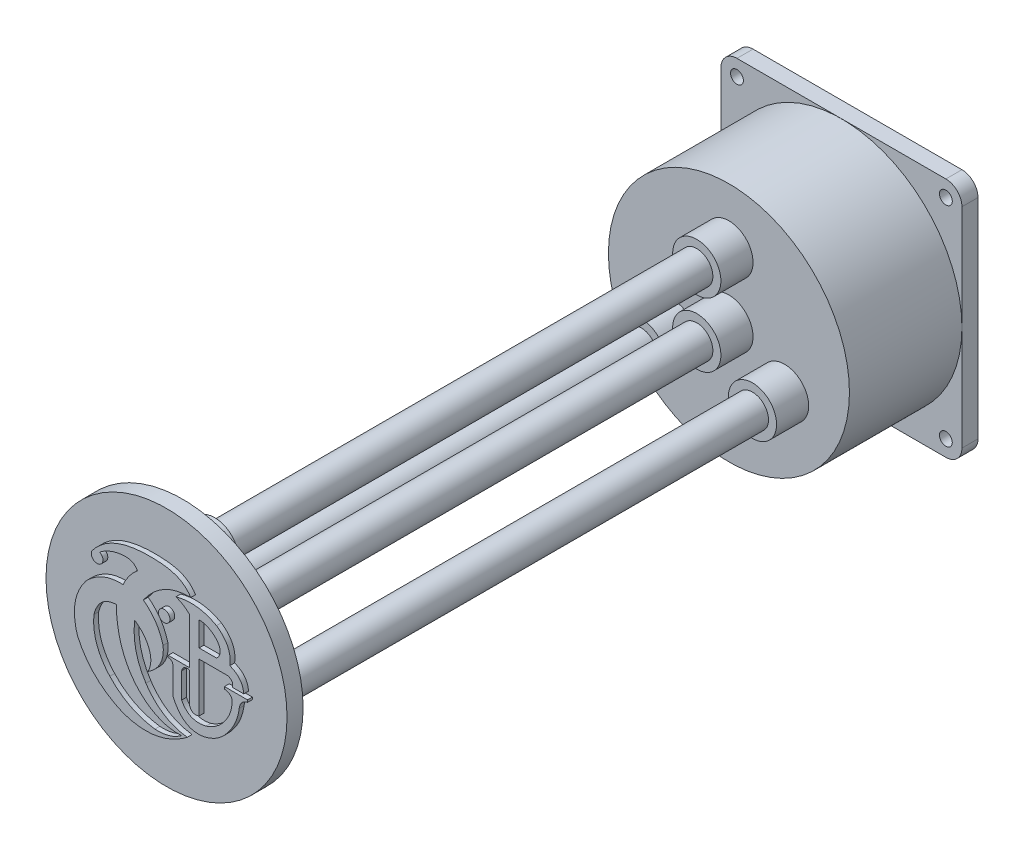
SolidWorks part; units mm, degrees
ref_plane "Plan de face" through (0, 0, 0) normal (0, 0, 1) x (1, 0, 0)
ref_plane "Plan de dessus" through (0, 0, 0) normal (0, 1, 0) x (1, 0, 0)
ref_plane "Plan de droite" through (0, 0, 0) normal (1, 0, 0) x (0, 0, -1)
sketch "Esquisse1" plane through (0, 0, 0) normal (0, 0, 1) x (1, 0, 0)
  circle A0 centre (0, 0) radius 75
extrude "Boss.-Extru.1" add sketch "Esquisse1" along normal blind 70
sketch "Esquisse2" plane through (0, 0, 70) normal (0, 0, 1) x (1, 0, 0)
  circle A0 centre (0, 0) radius 15
  circle A1 centre (0, 40) radius 15
  circle A3 centre (34.641, -20) radius 15
  circle A4 centre (-34.641, -20) radius 15
  dimension "D1" = 40
  dimension "D3" = 40
  dimension "D2" = 40
extrude "Boss.-Extru.2" add sketch "Esquisse2" along normal blind 20
sketch "Esquisse3" plane through (0, 0, 0) normal (0, 0, -1) x (-1, 0, 0)
  line L1 (-65, -75.0282) -> (65, -75.0282)
  line L2 (-75, -65.0282) -> (-75, 65.0282)
  line L3 (-65, 75.0282) -> (65, 75.0282)
  line L4 (75, -65.0282) -> (75, 65.0282)
  arc A0 (-75, -65.0282) -> (-65, -75.0282) centre (-65, -65.0282) ccw
  arc A1 (65, -75.0282) -> (75, -65.0282) centre (65, -65.0282) ccw
  arc A2 (75, 65.0282) -> (65, 75.0282) centre (65, 65.0282) ccw
  arc A3 (-75, 65.0282) -> (-65, 75.0282) centre (-65, 65.0282) cw
  circle A4 centre (-65, 65.0282) radius 4
  circle A5 centre (65, 65.0282) radius 4
  circle A6 centre (65, -65.0282) radius 4
  circle A7 centre (-65, -65.0282) radius 4
  point P0 (0, 0)
  dimension "D2" = 10
extrude "Boss.-Extru.3" add sketch "Esquisse3" along normal blind 10
sketch "Esquisse4" plane through (0, 0, 90) normal (0, 0, 1) x (1, 0, 0)
  circle A0 centre (0, 0) radius 10
  circle A1 centre (34.641, -20) radius 10
  circle A2 centre (0, 40) radius 10
  circle A3 centre (-34.641, -20) radius 10
extrude "Boss.-Extru.4" add sketch "Esquisse4" along normal blind 300
sketch "Esquisse5" plane through (0, 0, 390) normal (0, 0, 1) x (1, 0, 0)
  circle A0 centre (0, 0) radius 15
  circle A1 centre (34.641, -20) radius 15
  circle A2 centre (0, 40) radius 15
  circle A3 centre (-34.641, -20) radius 15
extrude "Boss.-Extru.5" add sketch "Esquisse5" along normal blind 20
sketch "Esquisse6" plane through (0, 0, 410) normal (0, 0, 1) x (1, 0, 0)
  circle A0 centre (0, 0) radius 75
extrude "Boss.-Extru.6" add sketch "Esquisse6" along normal blind 10
sketch "Esquisse7" plane through (0, 0, 420) normal (0, 0, 1) x (1, 0, 0)
  line L0 (32.3555, 186.539) -> (383.0221, 186.539) construction
  line L1 (53.4071, 0) -> (39.0486, 0)
  line L2 (39.0486, 0) -> (39.0486, -1.3877)
  line L3 (12.3957, -4.803) -> (12.3957, -20.6311)
  line L4 (53.4071, -1.3877) -> (53.4071, 0)
  line L5 (41.0751, 6.8898) -> (23.2507, 6.8898)
  line L6 (23.2507, 6.8898) -> (23.2507, -23.7682)
  line L7 (17.2507, -20.6311) -> (17.2507, -1.9366)
  line L8 (23.2507, 27.9939) -> (23.2507, 12.8898)
  line L9 (23.2507, 12.8898) -> (34.0879, 12.8898)
  line L10 (43.916, 2.0416) -> (51.0457, 2.0416)
  line L11 (4.0479, -1.8586) -> (4.0479, -0.6938)
  line L12 (6.9836, -4.803) -> (6.9836, -21.2808)
  line L13 (4.0479, -0.6938) -> (17.2507, -0.6938)
  line L14 (17.2507, -0.6938) -> (17.2507, 27.9939)
  arc A0 (-43.5586, 31.7503) -> (-38.6575, 33.6575) centre (-40.1927, 30.3516) ccw
  circle A1 centre (1.5513, 19.2737) radius 3.5764
  spline S0 degree 2 poles (41.0751, 6.8898) (45.0194, 5.7377) (43.916, 2.0416) knots 0 0 0 1 1 1
  spline S1 degree 2 poles (51.0457, 2.0416) (50.4252, 9.8675) (42.3971, 12.8898) knots 0 0 0 1 1 1
  spline S2 degree 3 poles (23.2507, 27.9939) (29.8659, 28.6425) (41.4001, 19.2845) (34.0879, 12.8898) knots 0 0 0 0 1 1 1 1
  spline S3 degree 2 poles (17.2507, -20.6311) (18.5783, -25.3636) (23.2507, -23.7682) knots 0 0 0 1 1 1
  spline S4 degree 2 poles (42.3971, 12.8898) (43.9337, 23.5711) (34.0879, 30.3516) knots 0 0 0 1 1 1
  spline S5 degree 2 poles (34.0879, 30.3516) (22.2894, 36.9655) (8.8224, 33.2489) knots 0 0 0 1 1 1
  spline S6 degree 2 poles (8.8224, 33.2489) (13.6767, 31.6734) (17.2507, 27.9939) knots 0 0 0 1 1 1
  spline S7 degree 2 poles (12.3957, -20.6311) (17.0826, -29.5664) (27.5697, -27.0832) knots 0 0 0 1 1 1
  spline S8 degree 2 poles (27.5697, -27.0832) (36.4416, -24.1134) (41.0751, -15.7186) knots 0 0 0 1 1 1
  spline S9 degree 2 poles (41.0751, -15.7186) (43.9138, -10.6368) (43.8417, -4.803) knots 0 0 0 1 1 1
  spline S10 degree 2 poles (43.8417, -4.803) (42.6771, -1.535) (39.0486, -1.3877) knots 0 0 0 1 1 1
  spline S11 degree 2 poles (53.4071, -1.3877) (48.9245, -2.341) (48.2204, -7.1836) knots 0 0 0 1 1 1
  spline S12 degree 2 poles (48.2204, -7.1836) (47.0221, -16.5321) (41.0751, -23.7682) knots 0 0 0 1 1 1
  spline S13 degree 2 poles (41.0751, -23.7682) (35.8278, -31.0943) (26.9307, -33.2683) knots 0 0 0 1 1 1
  spline S14 degree 2 poles (26.9307, -33.2683) (13.6978, -36.1928) (6.9836, -21.2808) knots 0 0 0 1 1 1
  spline S15 degree 2 poles (6.9836, -4.803) (6.8305, -1.8714) (4.0479, -1.8586) knots 0 0 0 1 1 1
  spline S16 degree 2 poles (12.3957, -4.803) (13.2863, -1.2072) (17.2507, -1.9366) knots 0 0 0 1 1 1
  spline S17 degree 2 poles (18.089, 37.508) (-0.1973, 37.7095) (-11.4151, 21.423) knots 0 0 0 1 1 1
  spline S18 degree 3 poles (18.089, 37.508) (13.0299, 45.3348) (-2.7473, 47.753) (-26.0193, 46.2095) (-38.3734, 38.6536) (-43.5586, 31.7503) knots 0 0 0 0 0.36306 0.660599 0.993992 0.993992 0.993992 0.993992
  spline S19 degree 2 poles (-15.1205, 35.2649) (-20.9397, 30.3937) (-24.0068, 23.4165) knots 0 0 0 1 1 1
  spline S20 degree 2 poles (-15.1205, 35.2649) (-17.2452, 39.431) (-22.42, 39.285) knots 0 0 0 1 1 1
  spline S21 degree 3 poles (-22.42, 39.285) (-28.2364, 39.1859) (-33.6629, 37.3549) (-38.5349, 33.7497) (-38.6575, 33.6575) knots 0 0 0 0 1 1.025906 1.025906 1.025906 1.025906
  spline S22 degree 2 poles (-24.0068, 23.4165) (-37.2444, 24.079) (-47.1121, 13.8446) knots 0 0 0 1 1 1
  spline S23 degree 2 poles (-47.1121, 13.8446) (-57.9906, -0.0058) (-52.428, -18.2781) knots 0 0 0 1 1 1
  spline S24 degree 2 poles (-52.428, -18.2781) (-43.9498, -37.2702) (-24.0068, -45.7743) knots 0 0 0 1 1 1
  spline S25 degree 2 poles (-24.0068, -45.7743) (-2.9509, -53.1338) (15.9036, -38.9336) knots 0 0 0 1 1 1
  spline S26 degree 2 poles (15.9036, -38.9336) (-0.3158, -36.9402) (-9.831, -22.6503) knots 0 0 0 1 1 1
  spline S27 degree 2 poles (-9.831, -22.6503) (-18.7963, -8.9145) (-16.8131, 7.8129) knots 0 0 0 1 1 1
  spline S28 degree 3 poles (-16.8131, 7.8129) (-9.387, 3.046) (-3.6964, -6.8235) (-8.6033, -15.7186) knots 0 0 0 0 1 1 1 1
  spline S29 degree 3 poles (-28.2844, 10.5657) (-28.1371, -0.9176) (-22.8824, -25.6862) (-0.4339, -40.8078) (12.3957, -39.7707) knots 0 0 0 0 0.484412 1 1 1 1
  spline S30 degree 2 poles (12.3957, -39.7707) (5.0711, -45.2053) (-4.2183, -44.5695) knots 0 0 0 1 1 1
  spline S31 degree 2 poles (-28.2844, 10.5657) (-39.1079, 10.2198) (-42.2103, -1.8586) knots 0 0 0 1 1 1
  spline S32 degree 2 poles (-42.2103, -1.8586) (-43.6323, -17.6774) (-32.2819, -30.1291) knots 0 0 0 1 1 1
  spline S33 degree 2 poles (-32.2819, -30.1291) (-21.127, -42.2327) (-4.2183, -44.5695) knots 0 0 0 1 1 1
  spline S34 degree 2 poles (-11.4151, 21.423) (-2.0812, 14.3278) (0.857, 3.0316) knots 0 0 0 1 1 1
  spline S35 degree 2 poles (0.857, 3.0316) (2.114, -8.8789) (-8.6033, -15.7186) knots 0 0 0 1 1 1
extrude "Boss.-Extru.7" add sketch "Esquisse7" along normal blind 3
